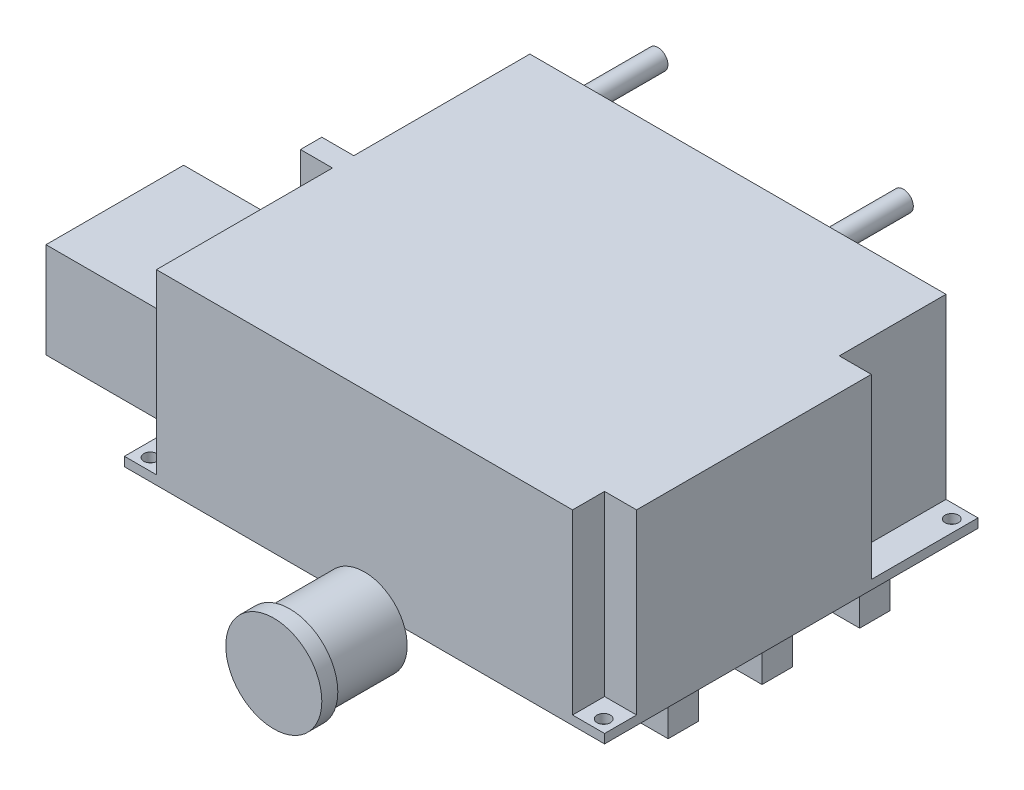
SolidWorks part; units mm, degrees
ref_plane "Front Plane" through (0, 0, 0) normal (0, 0, 1) x (1, 0, 0)
ref_plane "Top Plane" through (0, 0, 0) normal (0, 1, 0) x (1, 0, 0)
ref_plane "Right Plane" through (0, 0, 0) normal (1, 0, 0) x (0, 0, -1)
sketch "Sketch2" plane through (0, 0, 0) normal (0, 1, 0) x (1, 0, 0)
  line L1 (0, 0) -> (90, 0)
  line L2 (0, 0) -> (0, 70)
  line L3 (0, 70) -> (90, 70)
  line L4 (90, 0) -> (90, 70)
  dimension "D1" = 90
  dimension "D2" = 70
extrude "Boss-Extrude1" add sketch "Sketch2" along normal blind 35
sketch "Sketch4" plane through (0, 0, 0) normal (0, 0, 1) x (1, 0, 0)
  line L0 (0, 0) -> (90, 0) construction
  line L1 (90, 35) -> (90, 0) construction
  circle A0 centre (45, -2.57) radius 8
  dimension "D1" = 2.57
  dimension "D2" = 16
  dimension "D3" = 45
extrude "Boss-Extrude2" add sketch "Sketch4" along normal blind 14
sketch "Sketch6" plane through (0, 0, 0) normal (0, -1, 0) x (-1, 0, 0)
  line L0 (-90, 0) -> (-90, 70) construction
  line L1 (-78.52, 52.7) -> (-85.12, 52.7)
  line L2 (-78.52, 52.7) -> (-78.52, 58.4)
  line L3 (-78.52, 58.4) -> (-85.12, 58.4)
  line L4 (-85.12, 52.7) -> (-85.12, 58.4)
  line L5 (-90, 70) -> (0, 70) construction
  point P4 (-81.82, 52.7)
  point P5 (-85.12, 55.55)
  dimension "D1" = 5.7
  dimension "D2" = 6.6
  dimension "D3" = 4.88
  dimension "D4" = 11.6
sketch "Sketch7" plane through (0, 0, 0) normal (0, -1, 0) x (1, 0, 0)
  line L1 (85.12, -22.5) -> (78.52, -22.5)
  line L2 (85.12, -22.5) -> (85.12, -16.8)
  line L3 (85.12, -16.8) -> (78.52, -16.8)
  line L4 (78.52, -22.5) -> (78.52, -16.8)
  line L6 (0, 0) -> (37.424, 0) construction
  line L7 (90, 0) -> (90, -70) construction
  point P4 (81.82, -22.5)
  point P5 (78.52, -19.65)
  dimension "D1" = 5.7
  dimension "D2" = 6.6
  dimension "D3" = 16.8
  dimension "D4" = 4.88
sketch "Sketch10" plane through (0, 0, 0) normal (0, -1, 0) x (1, 0, 0)
  line L1 (85.12, -40.1) -> (78.52, -40.1)
  line L2 (85.12, -40.1) -> (85.12, -34.4)
  line L3 (85.12, -34.4) -> (78.52, -34.4)
  line L4 (78.52, -40.1) -> (78.52, -34.4)
  line L6 (78.52, -52.7) -> (85.12, -52.7) construction
  line L7 (90, 0) -> (90, -70) construction
  point P4 (81.82, -40.1)
  point P5 (78.52, -37.25)
  dimension "D1" = 5.7
  dimension "D2" = 6.6
  dimension "D3" = 12.6
  dimension "D4" = 4.88
extrude "Boss-Extrude3" add sketch "Sketch6" along normal blind 10
extrude "Boss-Extrude4" add sketch "Sketch10" along normal blind 10
extrude "Boss-Extrude5" add sketch "Sketch7" along normal blind 10
sketch "Sketch11" plane through (0, 35, 0) normal (0, 1, 0) x (1, 0, 0)
  line L0 (90, 0) -> (90, 70) construction
  line L1 (0, 0) -> (90, 0) construction
  circle A0 centre (87.55, 2.29) radius 1.25
  dimension "D1" = 2.45
  dimension "D3" = 2.5
  dimension "D2" = 2.29
sketch "Sketch12" plane through (0, 35, 0) normal (0, 1, 0) x (1, 0, 0)
  line L2 (90, 0) -> (90, 70) construction
  line L4 (90, 70) -> (0, 70) construction
  circle A0 centre (87.71, 67.37) radius 1.25
  dimension "D1" = 2.29
  dimension "D3" = 2.5
  dimension "D2" = 2.63
sketch "Sketch14" plane through (0, 35, 0) normal (0, 1, 0) x (1, 0, 0)
  line L2 (0, 0) -> (90, 0) construction
  line L3 (0, 70) -> (0, 0) construction
  circle A0 centre (2.63, 2.25) radius 1.25
  dimension "D1" = 2.25
  dimension "D3" = 2.5
  dimension "D2" = 2.63
sketch "Sketch15" plane through (0, 35, 0) normal (0, 1, 0) x (1, 0, 0)
  line L0 (90, 70) -> (0, 70) construction
  line L2 (0, 70) -> (0, 0) construction
  circle A0 centre (2.61, 67.35) radius 1.25
  dimension "D1" = 2.61
  dimension "D3" = 2.5
  dimension "D2" = 2.65
extrude "Cut-Extrude1" cut sketch "Sketch11" against normal through all both and the other way through all
extrude "Cut-Extrude2" cut sketch "Sketch15" against normal through all both and the other way through all
extrude "Cut-Extrude3" cut sketch "Sketch14" against normal through all both and the other way through all
extrude "Cut-Extrude4" cut sketch "Sketch12" against normal through all both and the other way through all
sketch "Sketch16" plane through (0, 35, 0) normal (0, 1, 0) x (1, 0, 0)
  line L1 (0, 70) -> (6, 70)
  line L2 (0, 70) -> (0, 37)
  line L3 (0, 37) -> (6, 37)
  line L4 (6, 70) -> (6, 37)
  dimension "D1" = 6
  dimension "D2" = 33
sketch "Sketch17" plane through (0, 35, 0) normal (0, 1, 0) x (1, 0, 0)
  line L0 (90, 0) -> (90, 70) construction
  line L1 (84, 70) -> (90, 70)
  line L2 (84, 70) -> (84, 50)
  line L3 (84, 50) -> (90, 50)
  line L4 (90, 70) -> (90, 50)
  line L5 (90, 70) -> (0, 70) construction
  dimension "D1" = 6
  dimension "D2" = 20
  dimension "D3" = 0
  dimension "D4" = 0
sketch "Sketch18" plane through (0, 35, 0) normal (0, 1, 0) x (1, 0, 0)
  line L0 (0, 0) -> (90, 0) construction
  line L1 (84, 6) -> (90, 6)
  line L2 (84, 6) -> (84, 0)
  line L3 (84, 0) -> (90, 0)
  line L4 (90, 6) -> (90, 0)
  line L5 (90, 0) -> (90, 70) construction
  dimension "D1" = 6
  dimension "D2" = 6
  dimension "D3" = 0
  dimension "D4" = 0
sketch "Sketch19" plane through (0, 35, 0) normal (0, 1, 0) x (1, 0, 0)
  line L1 (0, 33) -> (6, 33)
  line L2 (0, 33) -> (0, 0)
  line L3 (0, 0) -> (6, 0)
  line L4 (6, 33) -> (6, 0)
  line L6 (0, 70) -> (0, 0) construction
  line L7 (0, 0) -> (90, 0) construction
  dimension "D1" = 6
  dimension "D2" = 33
  dimension "D3" = 0
  dimension "D4" = 0
extrude "Cut-Extrude5" cut sketch "Sketch16" against normal offset from surface (33.3 mm away) 1.7 up to face at (87.71, 0, -68.62)
extrude "Cut-Extrude6" cut sketch "Sketch19" against normal offset from surface (33.3 mm away) 1.7 up to face at (87.71, 0, -68.62)
extrude "Cut-Extrude7" cut sketch "Sketch18" against normal offset from surface (33.3 mm away) 1.7 up to face at (87.71, 0, -68.62)
extrude "Cut-Extrude8" cut sketch "Sketch17" against normal offset from surface (33.3 mm away) 1.7 up to face at (87.71, 0, -68.62)
sketch "Sketch20" plane through (0, 0, 0) normal (1, 0, 0) x (0, 0, -1)
  line L1 (24.7, 4) -> (50.5, 4)
  line L2 (24.7, 4) -> (24.7, -13.9)
  line L3 (24.7, -13.9) -> (50.5, -13.9)
  line L4 (50.5, 4) -> (50.5, -13.9)
  line L5 (52.7, -10) -> (52.7, 0) construction
  line L6 (0, 0) -> (70, 0) construction
  dimension "D1" = 25.8
  dimension "D2" = 17.9
  dimension "D3" = 2.2
  dimension "D4" = 4
extrude "Boss-Extrude6" add sketch "Sketch20" against normal blind 39.4 contours L3 L4 L1 L2
sketch "Sketch27" plane through (0, 0, 14) normal (0, 0, 1) x (1, 0, 0)
  circle A0 centre (45, -2.57) radius 9
  dimension "D1" = 18
extrude "Boss-Extrude7" add sketch "Sketch27" along normal blind 3 contours A0
sketch "Sketch29" plane through (0, 4, 0) normal (0, 1, 0) x (1, 0, 0)
  line L0 (-39.4, 50.5) -> (0, 50.5) construction
  line L1 (-14.1, 50.5) -> (-12, 50.5)
  line L2 (-14.1, 50.5) -> (-14.1, 24.7)
  line L3 (-14.1, 24.7) -> (-12, 24.7)
  line L4 (-12, 50.5) -> (-12, 24.7)
  line L5 (-39.4, 24.7) -> (0, 24.7) construction
  line L6 (0, 37) -> (0, 33) construction
  dimension "D1" = 12
  dimension "D2" = 2.1
extrude "Cut-Extrude14" cut sketch "Sketch29" against normal blind 2.5
sketch "Sketch34" plane through (0, 0, -24.7) normal (0, 0, 1) x (1, 0, 0)
  line L0 (-39.4, -13.9) -> (0, -13.9) construction
  line L1 (-14.1, 1.5) -> (-12, 1.5)
  line L2 (-14.1, 1.5) -> (-14.1, -13.9)
  line L3 (-14.1, -13.9) -> (-12, -13.9)
  line L4 (-12, 1.5) -> (-12, -13.9)
  dimension "D1" = 2.1
extrude "Cut-Extrude15" cut sketch "Sketch34" against normal blind 2.5
sketch "Sketch35" plane through (0, -13.9, 0) normal (0, -1, 0) x (1, 0, 0)
  line L0 (-39.4, -50.5) -> (0, -50.5) construction
  line L1 (-14.1, -27.2) -> (-12, -27.2)
  line L2 (-14.1, -27.2) -> (-14.1, -50.5)
  line L3 (-14.1, -50.5) -> (-12, -50.5)
  line L4 (-12, -27.2) -> (-12, -50.5)
  dimension "D1" = 2.1
extrude "Cut-Extrude16" cut sketch "Sketch35" against normal blind 2.5
sketch "Sketch36" plane through (0, 0, -50.5) normal (0, 0, -1) x (-1, 0, 0)
  line L1 (12, 1.5) -> (14.1, 1.5)
  line L2 (12, 1.5) -> (12, -11.4)
  line L3 (12, -11.4) -> (14.1, -11.4)
  line L4 (14.1, 1.5) -> (14.1, -11.4)
extrude "Cut-Extrude17" cut sketch "Sketch36" against normal blind 2.5
sketch "Sketch38" plane through (0, 0, -70) normal (0, 0, -1) x (-1, 0, 0)
  line L0 (-90, 1.7) -> (-90, 35) construction
  line L2 (-90, 0) -> (0, 0) construction
  line L3 (0, 4) -> (0, 35) construction
  circle A0 centre (-56, 26.2) radius 1.875
  circle A1 centre (-10, 26.2) radius 1.875
  dimension "D1" = 3.75
  dimension "D4" = 3.75
  dimension "D2" = 34
  dimension "D3" = 26.2
  dimension "D5" = 26.2
  dimension "D6" = 10
extrude "Boss-Extrude8" add sketch "Sketch38" along normal blind 20
